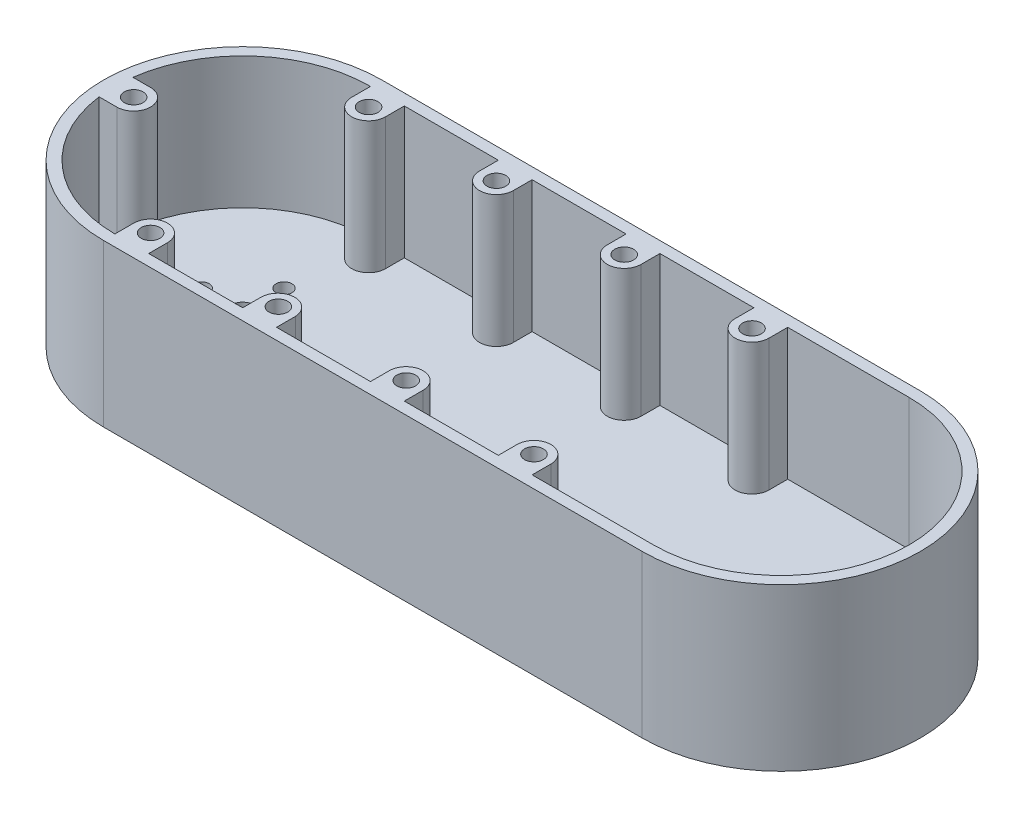
SolidWorks part; units mm, degrees
ref_plane "Front Plane" through (0, 0, 0) normal (0, 0, 1) x (1, 0, 0)
ref_plane "Top Plane" through (0, 0, 0) normal (0, 1, 0) x (1, 0, 0)
ref_plane "Right Plane" through (0, 0, 0) normal (1, 0, 0) x (0, 0, -1)
sketch "Sketch1" plane through (0, 0, 0) normal (0, 1, 0) x (1, 0, 0)
  circle A0 centre (0, 0) radius 15
extrude "Boss-Extrude1" add sketch "Sketch1" along normal blind 5
sketch "Sketch2" plane through (0, 5, 0) normal (0, 1, 0) x (1, 0, 0)
  line L2 (0, -37) -> (143.3, -37)
  line L4 (0, 37) -> (143.3, 37)
  arc A0 (0, 37) -> (0, -37) centre (0, 0) ccw
  arc A1 (143.3, 37) -> (143.3, -37) centre (143.3, 0) cw
  dimension "D2" = 143.3
extrude "Boss-Extrude2" add sketch "Sketch2" along normal blind 8
sketch "Sketch3" plane through (0, 13, 0) normal (0, 1, 0) x (1, 0, 0)
  line L0 (0, 34) -> (143.3, 34)
  line L1 (0, -34) -> (143.3, -34)
  arc A1 (143.3, 34) -> (143.3, -34) centre (143.3, 0) cw
  arc A2 (0, 34) -> (0, -34) centre (0, 0) ccw
  arc M2 (0, 37) -> (0, -37) centre (0, 0) ccw
  line M3 (0, -37) -> (143.3, -37)
  arc M4 (143.3, -37) -> (143.3, 37) centre (143.3, 0) ccw
  line M5 (143.3, 37) -> (0, 37)
  dimension "D1" = 143.3
extrude "Boss-Extrude3" add sketch "Sketch3" along normal blind 35 contours A2 L0 A1 L1 M5 M2 M3 M4
sketch "Sketch4" plane through (0, 13, 0) normal (0, 1, 0) x (1, 0, 0)
  circle A1 centre (0, 0) radius 15
  circle A2 centre (0, 10.9953) radius 2.1
  circle A3 centre (-11, 0) radius 2.1
  circle A4 centre (11, 0) radius 2.1
  circle A5 centre (0, -11) radius 2.1
  circle A6 centre (0, 0) radius 3.25
  dimension "D1" = 4.2
  dimension "D2" = 4.2
  dimension "D3" = 4.2
  dimension "D4" = 4.2
extrude "Cut-Extrude1" cut sketch "Sketch4" against normal blind 35 contours A3 | A6 | A2 | A4 | A5
sketch "Sketch5" plane through (0, 13, 0) normal (0, 1, 0) x (1, 0, 0)
  line L0 (0, 34) -> (0, 29)
  line L1 (0, -34) -> (0, -29)
  line L2 (9, 29) -> (9, 34)
  line L3 (0, 34) -> (143.3, 34) construction
  line L4 (9, -34) -> (34, -34)
  line L5 (9, -29) -> (9, -34)
  line L6 (0, -34) -> (143.3, -34) construction
  line L7 (0, -34) -> (143.3, -34) construction
  line L8 (34, -34) -> (34, -29)
  line L9 (43, -34) -> (68, -34)
  line L10 (43, -29) -> (43, -34)
  line L11 (68, -34) -> (68, -29)
  line L12 (77, -34) -> (102, -34)
  line L13 (77, -29) -> (77, -34)
  line L14 (102, -34) -> (102, -29)
  line L15 (9, 34) -> (34, 34)
  line L16 (111, -29) -> (111, -34)
  line L17 (43, 34) -> (68, 34)
  line L19 (68, 34) -> (68, 29)
  line L20 (34, 34) -> (34, 29)
  line L21 (77, 34) -> (102, 34)
  line L22 (43, 29) -> (43, 34)
  line L23 (77, 29) -> (77, 34)
  line L24 (102, 34) -> (102, 29)
  line L26 (111, 29) -> (111, 34)
  line L27 (-29, 4.5) -> (-33.75, 4.5)
  line L28 (-29, -4.5) -> (-33.7009, -4.5)
  circle A0 centre (4.5, 29) radius 2.5
  arc A1 (9, 29) -> (0, 29) centre (4.5, 29) cw
  circle A2 centre (143.3, 0) radius 29.58
  arc A3 (0, -29) -> (9, -29) centre (4.5, -29) cw
  circle A4 centre (4.5, -29) radius 2.5
  arc A5 (34, -29) -> (43, -29) centre (38.5, -29.1562) cw
  circle A6 centre (38.5, -29) radius 2.5
  arc A7 (68, -29) -> (77, -29) centre (72.5, -29) cw
  circle A8 centre (72.5, -29) radius 2.5
  arc A9 (102, -29) -> (111, -29) centre (106.5, -29) cw
  circle A10 centre (106.5, -29) radius 2.5
  arc A11 (34, 29) -> (43, 29) centre (38.5, 29) ccw
  circle A12 centre (38.5, 29) radius 2.5
  arc A13 (68, 29) -> (77, 29) centre (72.5, 29) ccw
  circle A14 centre (72.5, 29) radius 2.5
  arc A15 (102, 29) -> (111, 29) centre (106.5, 29) ccw
  circle A16 centre (106.5, 29) radius 2.5
  arc A17 (0, 34) -> (0, -34) centre (0, 0) ccw construction
  circle A18 centre (-29, 0) radius 2.5
  arc A20 (-29, 4.5) -> (-29, -4.5) centre (-29, 0) cw
  line M6 (143.3, 34) -> (0, 34)
  arc M7 (0, 34) -> (0, -34) centre (0, 0) ccw
  line M8 (0, -34) -> (143.3, -34)
  dimension "D1" = 59.16
extrude "Boss-Extrude4" add sketch "Sketch5" along normal blind 35 contours A20 L27 L28 A18 M7 | A1 L2 L0 A0 M6 | L20 A11 L22 A12 M6 | L19 A13 L23 A14 M6 | A7 L11 L13 A8 M8 | A5 L8 L10 A6 M8 | A3 L1 L5 A4 M8 | L24 A15 L26 A16 M6 | A9 L14 L16 A10 M8
